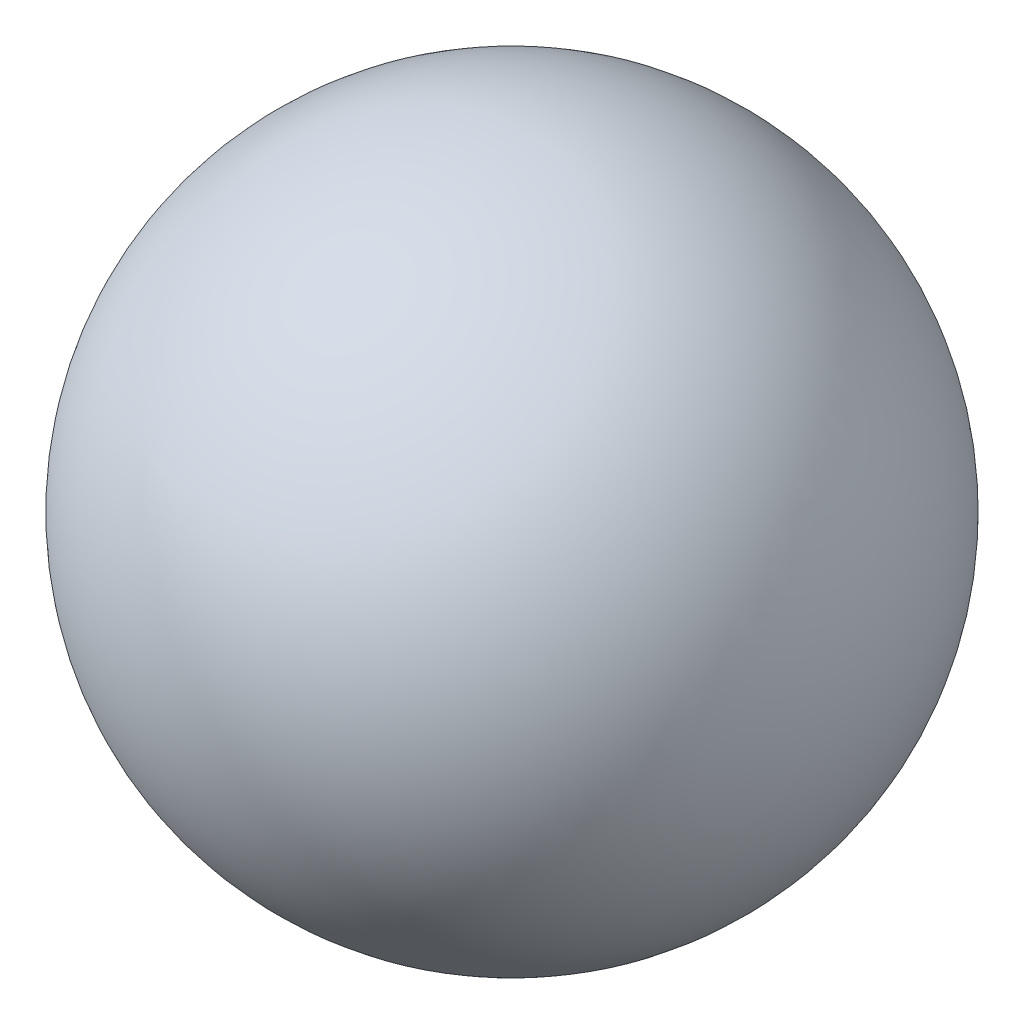
SolidWorks part; units mm, degrees
ref_plane "Front Plane" through (0, 0, 0) normal (0, 0, 1) x (1, 0, 0)
ref_plane "Top Plane" through (0, 0, 0) normal (0, 1, 0) x (1, 0, 0)
ref_plane "Right Plane" through (0, 0, 0) normal (1, 0, 0) x (0, 0, -1)
sketch "Sketch1" plane through (0, 0, 0) normal (0, 0, 1) x (1, 0, 0)
  line L0 (0, 0) -> (0, 2.3846) construction
  line L1 (0, 1.86) -> (0, -1.86)
  arc A0 (0, 1.86) -> (0, -1.86) centre (0, 0) cw
  dimension "D1" = 1.86
revolve "Revolve1" add sketch "Sketch1" angle 360 about L0
